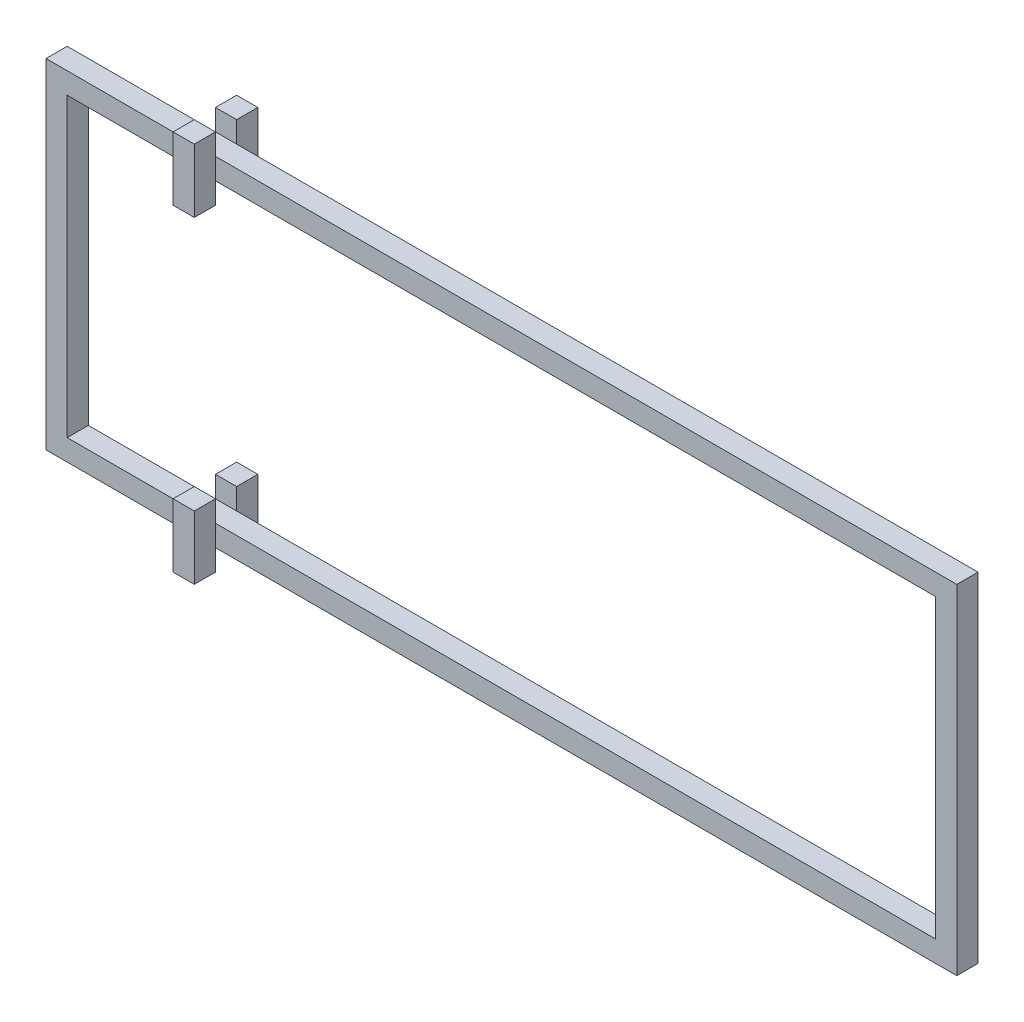
SolidWorks part; units mm, degrees
ref_plane "Front" through (0, 0, 0) normal (0, 0, 1) x (1, 0, 0)
ref_plane "Top" through (0, 0, 0) normal (0, 1, 0) x (1, 0, 0)
ref_plane "Right" through (0, 0, 0) normal (1, 0, 0) x (0, 0, -1)
sketch "Sketch1" plane through (0, 0, 0) normal (0, 0, 1) x (1, 0, 0)
  line L1 (0, 0) -> (-109.22, 0)
  line L2 (0, 0) -> (0, 40.64)
  line L3 (0, 40.64) -> (-109.22, 40.64)
  line L4 (-109.22, 0) -> (-109.22, 40.64)
  line L5 (-106.68, 38.1) -> (-2.54, 38.1)
  line L6 (-106.68, 38.1) -> (-106.68, 2.54)
  line L7 (-106.68, 2.54) -> (-2.54, 2.54)
  line L8 (-2.54, 38.1) -> (-2.54, 2.54)
  dimension "D1" = 109.22
  dimension "D2" = 40.64
  dimension "D3" = 2.54
  dimension "D4" = 2.54
  dimension "D5" = 2.54
  dimension "D6" = 2.54
extrude "Boss-Extrude1" add sketch "Sketch1" along normal blind 2.54
sketch "Sketch2" plane through (0, 0, 0) normal (0, 0, -1) x (-1, 0, 0)
  line L0 (109.22, 40.64) -> (109.22, 0) construction
  line L1 (88.9, 38.1) -> (91.44, 38.1)
  line L2 (88.9, 38.1) -> (88.9, 40.64)
  line L3 (88.9, 40.64) -> (91.44, 40.64)
  line L4 (91.44, 38.1) -> (91.44, 40.64)
  line L5 (91.44, 0) -> (88.9, 0)
  line L6 (91.44, 0) -> (91.44, 2.54)
  line L7 (91.44, 2.54) -> (88.9, 2.54)
  line L8 (88.9, 0) -> (88.9, 2.54)
  line L9 (109.22, 0) -> (0, 0) construction
  line L10 (106.68, 2.54) -> (2.54, 2.54) construction
  line L11 (0, 40.64) -> (109.22, 40.64) construction
  dimension "D1" = 17.78
extrude "Boss-Extrude2" add sketch "Sketch2" along normal blind 2.54
ref_plane "Plane1" through (0, 0, 1.27) normal (0, 0, 1) x (1, 0, 0)
mirror "Mirror1" about plane through (0, 0, 1.27) normal (0, 0, 1) of "Boss-Extrude2"
sketch "Sketch4" plane through (0, 40.64, 0) normal (0, 1, 0) x (1, 0, 0)
  line L0 (-88.9, -5.08) -> (-88.9, -2.54) construction
  line L1 (-91.44, 2.54) -> (-88.9, 2.54)
  line L2 (-91.44, 2.54) -> (-91.44, 0)
  line L3 (-91.44, 0) -> (-88.9, 0)
  line L4 (-88.9, 2.54) -> (-88.9, 0)
  line L5 (-91.44, -5.08) -> (-88.9, -5.08)
  line L6 (-91.44, -5.08) -> (-91.44, -2.54)
  line L7 (-91.44, -2.54) -> (-88.9, -2.54)
  line L8 (-88.9, -5.08) -> (-88.9, -2.54)
  line L13 (0, -2.54) -> (-88.9, -2.54) construction
  line L14 (-91.44, -5.08) -> (-91.44, -2.54) construction
  line L15 (0, 0) -> (-88.9, 0) construction
  line L17 (-88.9, 2.54) -> (-88.9, 0) construction
  line L18 (-91.44, 2.54) -> (-88.9, 2.54) construction
  point P14 (0, 0)
  point P15 (-109.22, 38.1)
  point P16 (0, 0)
  point P19 (0, 0)
extrude "Boss-Extrude3" add sketch "Sketch4" along normal blind 2.54
sketch "Sketch6" plane through (0, 38.1, 0) normal (0, -1, 0) x (-1, 0, 0)
  line L1 (88.9, 2.54) -> (91.44, 2.54)
  line L2 (88.9, 2.54) -> (88.9, 0)
  line L3 (88.9, 0) -> (91.44, 0)
  line L4 (91.44, 2.54) -> (91.44, 0)
  line L5 (88.9, -5.08) -> (91.44, -5.08)
  line L6 (88.9, -5.08) -> (88.9, -2.54)
  line L7 (88.9, -2.54) -> (91.44, -2.54)
  line L8 (91.44, -5.08) -> (91.44, -2.54)
extrude "Boss-Extrude4" add sketch "Sketch6" along normal blind 2.54
ref_plane "Plane2" through (0, 20.32, 0) normal (0, -1, 0) x (-1, 0, 0)
mirror "Mirror3" about plane through (0, 20.32, 0) normal (0, -1, 0) of "Boss-Extrude4", "Boss-Extrude3"
